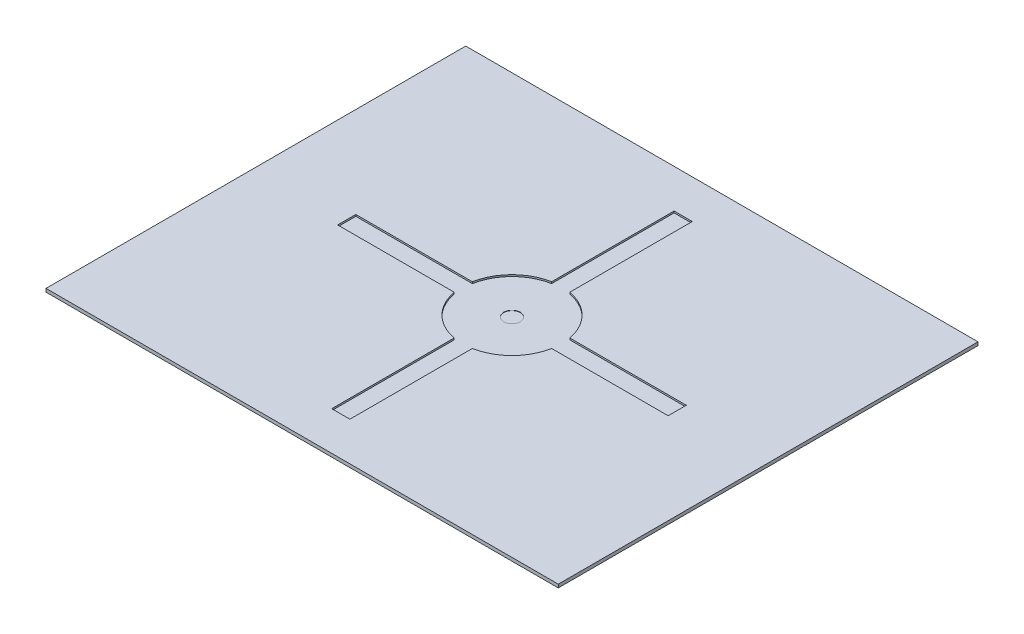
SolidWorks part; units mm, degrees
ref_plane "Front Plane" through (0, 0, 0) normal (0, 0, 1) x (1, 0, 0)
ref_plane "Top Plane" through (0, 0, 0) normal (0, 1, 0) x (1, 0, 0)
ref_plane "Right Plane" through (0, 0, 0) normal (1, 0, 0) x (0, 0, -1)
sketch "Sketch1" plane through (0, 0, 0) normal (0, 1, 0) x (1, 0, 0)
  line L1 (-77.5, 63.5) -> (77.5, 63.5)
  line L2 (-77.5, 63.5) -> (-77.5, -63.5)
  line L3 (-77.5, -63.5) -> (77.5, -63.5)
  line L4 (77.5, 63.5) -> (77.5, -63.5)
  line L5 (-77.5, 63.5) -> (77.5, -63.5) construction
  line L6 (-77.5, -63.5) -> (77.5, 63.5) construction
  point P0 (0, 0)
  dimension "D1" = 127
  dimension "D2" = 155
extrude "Boss-Extrude1" add sketch "Sketch1" along normal blind 1
sketch "Sketch2" plane through (0, 1, 0) normal (0, 1, 0) x (1, 0, 0)
  line L0 (2.75, -14.7458) -> (2.75, -51.7988)
  line L1 (-50, 2.75) -> (-14.7458, 2.75)
  line L2 (-50, 2.75) -> (-50, -2.75)
  line L3 (-50, -2.75) -> (-14.7458, -2.75)
  line L4 (50, 2.75) -> (50, -2.75)
  line L5 (-50, 2.75) -> (50, -2.75) construction
  line L6 (-50, -2.75) -> (50, 2.75) construction
  line L7 (-2.75, 51.7988) -> (2.75, 51.7988)
  line L8 (-2.75, 51.7988) -> (-2.75, 14.7458)
  line L9 (-2.75, -51.7988) -> (2.75, -51.7988)
  line L10 (2.75, 51.7988) -> (2.75, 14.7458)
  line L11 (-2.75, 51.7988) -> (2.75, -51.7988) construction
  line L12 (-2.75, -51.7988) -> (2.75, 51.7988) construction
  line L13 (-2.75, -14.7458) -> (-2.75, -51.7988)
  line L18 (14.7458, 2.75) -> (50, 2.75)
  line L19 (14.7458, -2.75) -> (50, -2.75)
  arc A0 (-2.75, 14.7458) -> (-14.7458, 2.75) centre (0, 0) ccw
  arc A1 (14.7458, 2.75) -> (2.75, 14.7458) centre (0, 0) ccw
  arc A2 (2.75, -14.7458) -> (14.7458, -2.75) centre (0, 0) ccw
  arc A3 (-14.7458, -2.75) -> (-2.75, -14.7458) centre (0, 0) ccw
  dimension "D4" = 30
  dimension "D1" = 100
  dimension "D2" = 5.5
  dimension "D3" = 5.5
  dimension "D5" = 100
extrude "Cut-Extrude1" cut sketch "Sketch2" against normal blind 0.5
sketch "Sketch3" plane through (0, 0.5, 0) normal (0, 1, 0) x (1, 0, 0)
  circle A0 centre (0, 0) radius 2.5
  dimension "D1" = 5
extrude "Cut-Extrude2" cut sketch "Sketch3" against normal blind 0.1
